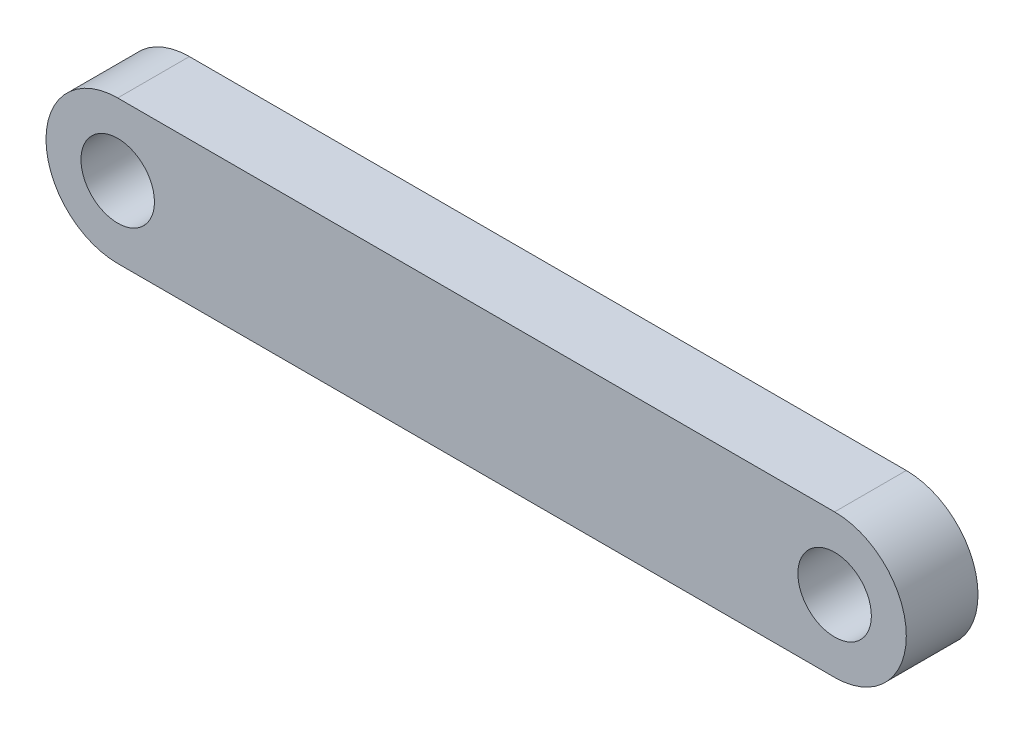
SolidWorks part; units mm, degrees
ref_plane "정면" through (0, 0, 0) normal (0, 0, 1) x (1, 0, 0)
ref_plane "윗면" through (0, 0, 0) normal (0, 1, 0) x (1, 0, 0)
ref_plane "우측면" through (0, 0, 0) normal (1, 0, 0) x (0, 0, -1)
sketch "스케치1" plane through (0, 0, 0) normal (0, 0, 1) x (1, 0, 0)
  line L0 (0, 0) -> (40, 0) construction
  line L1 (0, 4) -> (40, 4)
  line L2 (0, -4) -> (40, -4)
  arc A0 (0, 4) -> (0, -4) centre (0, 0) ccw
  arc A1 (40, -4) -> (40, 4) centre (40, 0) ccw
  circle A2 centre (0, 0) radius 2.05
  circle A3 centre (40, 0) radius 2.05
  point P3 (20, 0)
  dimension "D1" = 4.1
  dimension "D2" = 4.1
  dimension "D4" = 4
  dimension "D3" = 40
extrude "보스-돌출1" add sketch "스케치1" along normal blind 4
